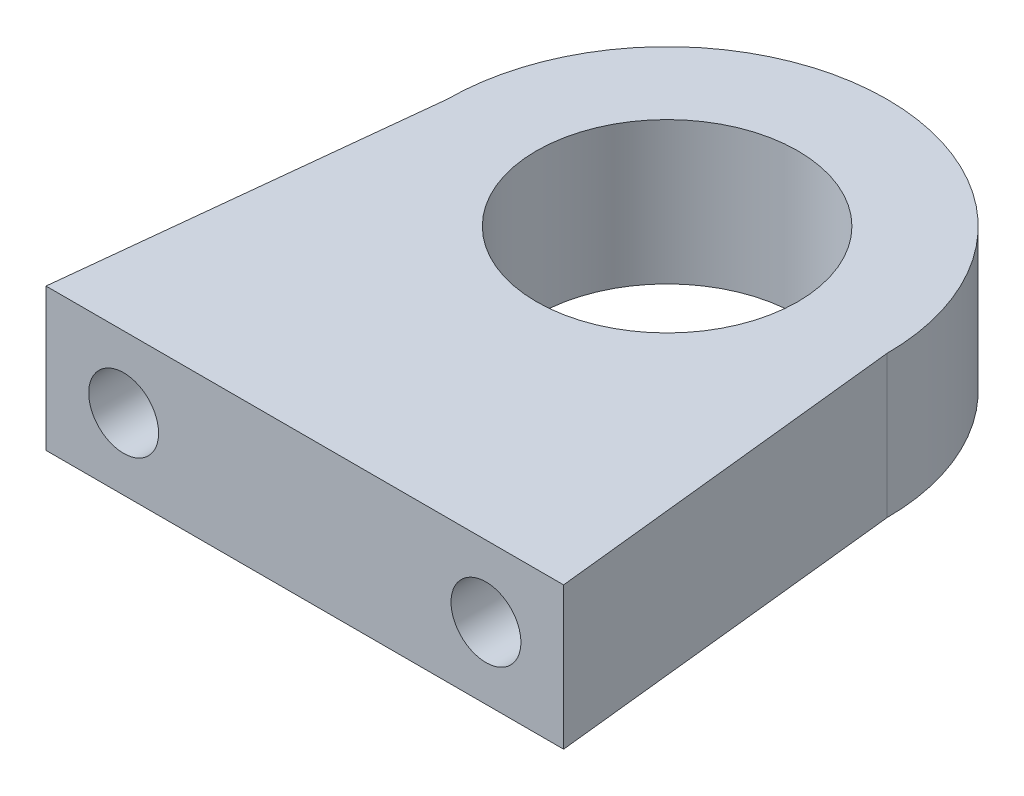
SolidWorks part; units mm, degrees
ref_plane "Front Plane" through (0, 0, 0) normal (0, 0, 1) x (1, 0, 0)
ref_plane "Top Plane" through (0, 0, 0) normal (0, 1, 0) x (1, 0, 0)
ref_plane "Right Plane" through (0, 0, 0) normal (1, 0, 0) x (0, 0, -1)
sketch "Sketch1" plane through (0, 0, 0) normal (0, 1, 0) x (1, 0, 0)
  line L0 (-10, 0) -> (-8.5, 14)
  line L1 (-10, 0) -> (10, 0)
  line L2 (10, 0) -> (8.5, 14)
  line L3 (-8.5, 14) -> (8.5, 14) construction
  line L4 (0, 14) -> (0, 0) construction
  arc A0 (-8.5, 14) -> (8.5, 14) centre (0, 14) cw
  circle A1 centre (0, 14) radius 5.05
  dimension "D1" = 8.5
  dimension "D3" = 14
  dimension "D4" = 10.1
  dimension "D2" = 20
extrude "Boss-Extrude1" add sketch "Sketch1" along normal blind 5.5
sketch "Sketch2" plane through (0, 0, 0) normal (0, 0, 1) x (1, 0, 0)
  line L0 (-10, 2.75) -> (10, 2.75) construction
  line L1 (-10, 5.5) -> (-10, 0) construction
  line L2 (10, 5.5) -> (10, 0) construction
  line L3 (0, 0) -> (0, 5.5) construction
  line L4 (-10, 0) -> (10, 0) construction
  line L5 (-10, 5.5) -> (10, 5.5) construction
  circle A0 centre (-7, 2.75) radius 1.35
  circle A2 centre (7, 2.75) radius 1.35
  dimension "D1" = 2.7
  dimension "D2" = 7
extrude "Cut-Extrude1" cut sketch "Sketch2" against normal blind 10
